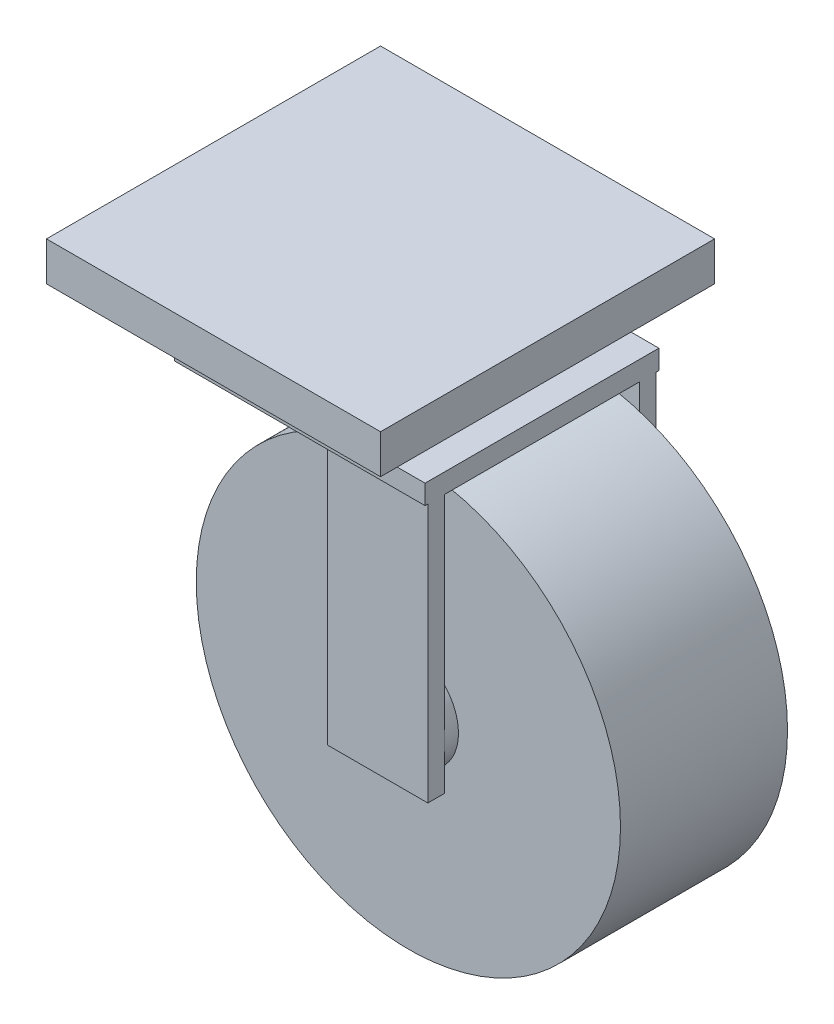
SolidWorks part; units mm, degrees
ref_plane "Front Plane" through (0, 0, 0) normal (0, 0, 1) x (1, 0, 0)
ref_plane "Top Plane" through (0, 0, 0) normal (0, 1, 0) x (1, 0, 0)
ref_plane "Right Plane" through (0, 0, 0) normal (1, 0, 0) x (0, 0, -1)
sketch "SK_P01_Spacer4mm" plane through (0, 0, 0) normal (0, 1, 0) x (1, 0, 0)
  line L0 (-44.05, -30) -> (15.95, -30)
  line L1 (15.95, -30) -> (15.95, 30)
  line L2 (15.95, 30) -> (-44.05, 30)
  line L3 (-44.05, 30) -> (-44.05, -30)
extrude "P01_Spacer4mm" add sketch "SK_P01_Spacer4mm" along normal blind 4 from offset 89
sketch "SK_P02_Topplate" plane through (0, 0, 0) normal (0, 1, 0) x (1, 0, 0)
  line L0 (-44.05, -30) -> (15.95, -30)
  line L1 (15.95, -30) -> (15.95, 30)
  line L2 (15.95, 30) -> (-44.05, 30)
  line L3 (-44.05, 30) -> (-44.05, -30)
extrude "P02_Topplate" add sketch "SK_P02_Topplate" along normal blind 3 from offset 86
sketch "SK_P03_Swivelrace" plane through (0, 0, 0) normal (0, 1, 0) x (1, 0, 0)
  circle A0 centre (-14.05, 0) radius 22
extrude "P03_Swivelrace" add sketch "SK_P03_Swivelrace" along normal blind 6 from offset 80
sketch "SK_P04_Forkyoke" plane through (0, 0, 0) normal (0, 1, 0) x (1, 0, 0)
  line L0 (-30.05, -21) -> (14.95, -21)
  line L1 (14.95, -21) -> (14.95, 21)
  line L2 (14.95, 21) -> (-30.05, 21)
  line L3 (-30.05, 21) -> (-30.05, -21)
extrude "P04_Forkyoke" add sketch "SK_P04_Forkyoke" along normal blind 3.5 from offset 76.5
sketch "SK_P05_Forkleg" plane through (0, 0, 0) normal (0, 1, 0) x (1, 0, 0)
  line L0 (-3.05, 17.5) -> (14.95, 17.5)
  line L1 (14.95, 17.5) -> (14.95, 20.5)
  line L2 (14.95, 20.5) -> (-3.05, 20.5)
  line L3 (-3.05, 20.5) -> (-3.05, 17.5)
extrude "P05_Forkleg" add sketch "SK_P05_Forkleg" along normal blind 48 from offset 30
sketch "SK_P06_Forkleg" plane through (0, 0, 0) normal (0, 1, 0) x (1, 0, 0)
  line L0 (-3.05, -20.5) -> (14.95, -20.5)
  line L1 (14.95, -20.5) -> (14.95, -17.5)
  line L2 (14.95, -17.5) -> (-3.05, -17.5)
  line L3 (-3.05, -17.5) -> (-3.05, -20.5)
extrude "P06_Forkleg" add sketch "SK_P06_Forkleg" along normal blind 48 from offset 30
sketch "SK_P07_Wheel3in" plane through (0, 0, 0) normal (0, 0, 1) x (1, 0, 0)
  circle A0 centre (5.95, 38.1) radius 38.1
extrude "P07_Wheel3in" add sketch "SK_P07_Wheel3in" along normal blind 30 from offset 15
sketch "SK_P08_Axle" plane through (0, 0, 0) normal (0, 0, 1) x (1, 0, 0)
  circle A0 centre (5.95, 38.1) radius 9
extrude "P08_Axle" add sketch "SK_P08_Axle" along normal blind 35 from offset 17.5
